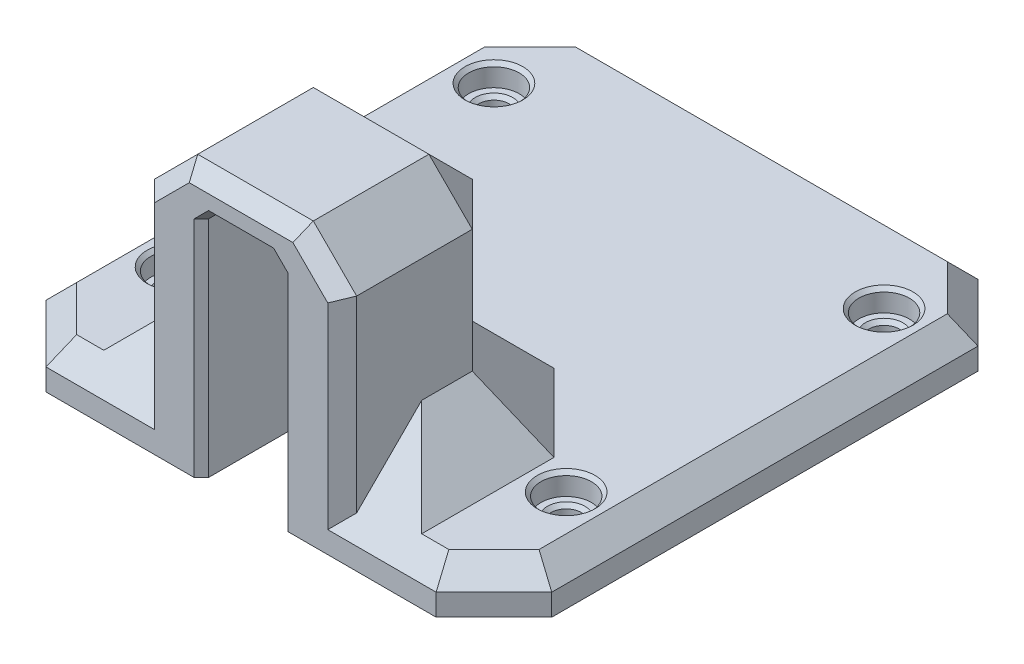
SolidWorks part; units mm, degrees
material "ABS"
ref_plane "Front Plane" through (0, 0, 0) normal (0, 0, 1) x (1, 0, 0)
ref_plane "Top Plane" through (0, 0, 0) normal (0, 1, 0) x (1, 0, 0)
ref_plane "Right Plane" through (0, 0, 0) normal (1, 0, 0) x (0, 0, -1)
sketch "Sketch1" plane through (0, 0, 0) normal (0, 1, 0) x (1, 0, 0)
  line L0 (-35, 27) -> (-27, 35)
  line L1 (-27, 35) -> (27, 35)
  line L2 (-35, 27) -> (-35, -32)
  line L4 (35, 27) -> (35, -32)
  line L5 (27, 35) -> (35, 27)
  line L6 (27, -40) -> (35, -32)
  line L7 (-35, -32) -> (-27, -40)
  line L8 (-1000, 0) -> (49000, 0) construction
  line L9 (0, -1000) -> (0, 49000) construction
  line L11 (-5, -40) -> (-5, -27.65) construction
  line L13 (5, -27.65) -> (5, -40) construction
  line L15 (-5.5, -40) -> (-5.5, -27.8571)
  line L17 (-5.5, -27.8571) -> (-9.5, -23.8571)
  line L18 (-5, -27.65) -> (-9, -23.65) construction
  line L19 (-9, -23.65) -> (-9, -21.15) construction
  line L20 (-9, -21.15) -> (9, -21.15) construction
  line L21 (9, -21.15) -> (9, -23.65) construction
  line L22 (9, -23.65) -> (5, -27.65) construction
  line L23 (-9.5, -23.8571) -> (-9.5, -20.65)
  line L24 (-9.5, -20.65) -> (9.5, -20.65)
  line L25 (9.5, -20.65) -> (9.5, -23.8571)
  line L26 (9.5, -23.8571) -> (5.5, -27.8571)
  line L27 (5.5, -27.8571) -> (5.5, -40)
  line L28 (-27, -40) -> (-5.5, -40)
  line L29 (5.5, -40) -> (27, -40)
  circle A0 centre (-27, 22) radius 2.1
  circle A1 centre (27, 22) radius 2.1
  circle A2 centre (27, -22) radius 2.1
  circle A3 centre (-27, -22) radius 2.1
  point P1 (0, 35)
  point P36 (0, -21.15)
  dimension "D7" = 4.2
  dimension "D1" = 75
  dimension "D2" = 70
  dimension "D3" = 35
  dimension "D4" = 8
  dimension "D5" = 27
  dimension "D6" = 22
  dimension "D8" = 18.85
  dimension "D9" = 18
  dimension "D10" = 4
  dimension "D11" = 2.5
  dimension "D12" = 0.5
extrude "Main Cap Extrude" add sketch "Sketch1" along normal blind 6
chamfer "Main Body Chamfer" distance 3 angle 45 9 edges at (16.25, 6, 40) (31, 6, 36) (35, 6, 2.5) (31, 6, -31) (0, 6, -35) (-31, 6, -31) (-35, 6, 2.5) (-31, 6, 36) (-16.25, 6, 40)
sketch "Sketch4" plane through (0, 6, 0) normal (0, 1, 0) x (1, 0, 0)
  circle A0 centre (-27, 22) radius 3.5
  circle A1 centre (-27, -22) radius 3.5
  circle A2 centre (27, -22) radius 3.5
  circle A3 centre (27, 22) radius 3.5
  dimension "D1" = 7
extrude "Hole Countersink Cut" cut sketch "Sketch4" against normal blind 3
chamfer "Hole Countersink Chamfer" distance 0.5 angle 45 8 edges at (27, 3, -19.9) (27, 3, 24.1) (-27, 3, 24.1) (-27, 3, -19.9) (-27, 6, 25.5) (-27, 6, -18.5) (27, 6, 25.5) (27, 6, -18.5)
sketch "Sketch2" plane through (0, 0, 0) normal (0, 1, 0) x (1, 0, 0)
  line L0 (5.5, -27.8571) -> (5.5, -37) construction
  line L1 (9.5, -23.8571) -> (5.5, -27.8571) construction
  line L2 (9.5, -20.65) -> (9.5, -23.8571) construction
  line L3 (-9.5, -20.65) -> (9.5, -20.65) construction
  line L4 (-9.5, -23.8571) -> (-9.5, -20.65) construction
  line L5 (-5.5, -27.8571) -> (-9.5, -23.8571) construction
  line L6 (-5.5, -37) -> (-5.5, -27.8571) construction
  line L7 (5.5, -27.8571) -> (5.5, -40)
  line L8 (9.5, -23.8571) -> (5.5, -27.8571)
  line L9 (9.5, -20.65) -> (9.5, -23.8571)
  line L10 (-9.5, -20.65) -> (9.5, -20.65)
  line L11 (-9.5, -23.8571) -> (-9.5, -20.65)
  line L12 (-5.5, -27.8571) -> (-9.5, -23.8571)
  line L13 (-5.5, -40) -> (-5.5, -27.8571)
  line L14 (-14, -40) -> (-14, -16)
  line L15 (-27, -40) -> (-5.5, -40) construction
  line L16 (-14, -16) -> (14, -16)
  line L17 (14, -16) -> (14, -40)
  line L18 (5.5, -40) -> (27, -40) construction
  line L19 (14, -40) -> (5.5, -40)
  line L20 (-5.5, -40) -> (-14, -40)
  dimension "D1" = 28
  dimension "D2" = 24
extrude "Main Pinion Chimney Extrude" add sketch "Sketch2" along normal offset from surface (32 mm away) 32 up to face at (0, 0, 15.2955)
sketch "Sketch3" plane through (0, 32, 0) normal (0, 1, 0) x (1, 0, 0)
  line L0 (-14, -16) -> (14, -16)
  line L1 (14, -16) -> (14, -40)
  line L2 (14, -40) -> (-14, -40)
  line L3 (-14, -40) -> (-14, -16)
extrude "Pinion Chimney Cap Extrude" add sketch "Sketch3" along normal blind 5
chamfer "Internal Chimney Chamfer" distance 1 angle 45 10 edges at (9.5, 32, 22.2536) (0, 32, 20.65) (-9.5, 32, 22.2536) (-7.5, 32, 25.8571) (-5.5, 32, 33.9286) (-5.5, 16, 40) (0, 32, 40) (7.5, 32, 25.8571) (5.5, 32, 33.9286) (5.5, 16, 40)
chamfer "Main Chimney External Chamfer" distance 6 angle 45 5 edges at (-14, 37, 28) (14, 37, 28) (-14, 21.5, 16) (14, 21.5, 16) (0, 37, 16)
chamfer "Chimney Plate Chamfer" distance 8 angle 45 5 edges at (14, 6, 29.5) (11, 6, 19) (0, 6, 16) (-11, 6, 19) (-14, 6, 29.5)
chamfer "Chimney Front Chamfer" distance 2 angle 45 5 edges at (14, 17, 40) (11, 34, 40) (0, 37, 40) (-11, 34, 40) (-14, 17, 40)
